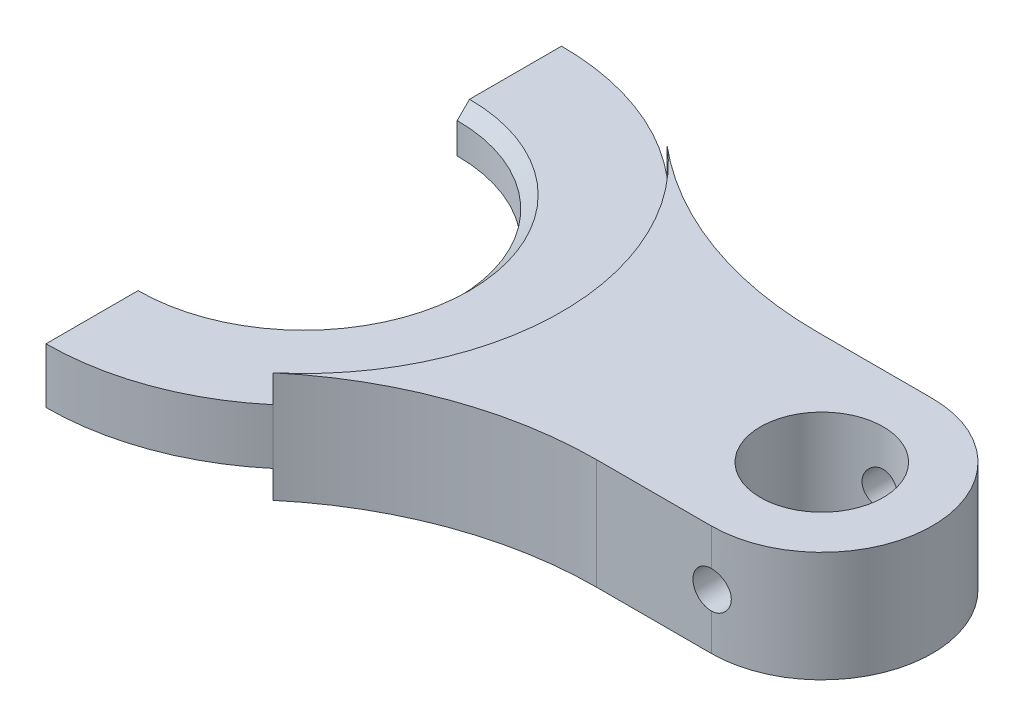
SolidWorks part; units mm, degrees
ref_plane "前视基准面" through (0, 0, 0) normal (0, 0, 1) x (1, 0, 0)
ref_plane "上视基准面" through (0, 0, 0) normal (0, 1, 0) x (1, 0, 0)
ref_plane "右视基准面" through (0, 0, 0) normal (1, 0, 0) x (0, 0, -1)
other "Configuration Table"
sketch "草图1" plane through (0, 0, 0) normal (0, 1, 0) x (1, 0, 0)
  line L0 (0, 9) -> (-9.3366, 9)
  line L1 (0, -9) -> (-9.3366, -9)
  line L2 (-42.2, 21) -> (-42.2, 12.5)
  line L3 (-42.2, -12.5) -> (-42.2, -21)
  arc A0 (0, -9) -> (0, 9) centre (0, 0) ccw
  arc A1 (-28.668, 16.0588) -> (-42.2, 21) centre (-42.2, 0) ccw
  arc A2 (-9.3366, 9) -> (-28.668, 16.0588) centre (-9.3366, 39) cw
  arc A3 (-9.3366, -9) -> (-28.668, -16.0588) centre (-9.3366, -39) ccw
  circle A4 centre (0, 0) radius 5
  arc A5 (-42.2, -12.5) -> (-42.2, 12.5) centre (-42.2, 0) ccw
  arc A6 (-42.2, -21) -> (-28.668, -16.0588) centre (-42.2, 0) ccw
  dimension "D1" = 18
  dimension "D2" = 42
  dimension "D3" = 42.2
  dimension "D4" = 30
  dimension "D5" = 10
  dimension "D6" = 25
extrude "凸台-拉伸1" add sketch "草图1" along normal mid plane 9
sketch "草图2" plane through (0, 4.5, 0) normal (0, 1, 0) x (1, 0, 0)
  line L0 (-42.2, -12.5) -> (-42.2, -21) construction
  line L1 (-42.2, 21) -> (-42.2, 12.5) construction
  line L2 (-42.2, -12.5) -> (-42.2, -21)
  line L3 (-42.2, 21) -> (-42.2, 12.5)
  arc A0 (-28.668, 16.0588) -> (-42.2, 21) centre (-42.2, 0) ccw construction
  arc A1 (-42.2, -21) -> (-42.2, 21) centre (-42.2, 0) ccw
  arc A3 (-42.2, -12.5) -> (-42.2, 12.5) centre (-42.2, 0) ccw construction
  arc A4 (-42.2, -12.5) -> (-42.2, 12.5) centre (-42.2, 0) ccw
  point P3 (-42.2, -21)
extrude "切除-拉伸1" cut sketch "草图2" against normal blind 2.25
mirror "镜向1" about plane through (0, 0, 0) normal (0, 1, 0) of "切除-拉伸1"
chamfer "倒角1" distance 1 angle 45 2 edges at (-29.7, -2.25, 0) (-29.7, 2.25, 0)
sketch "草图3" plane through (0, 0, 0) normal (0, 0, 1) x (1, 0, 0)
  circle A0 centre (0, 0) radius 1.5
  dimension "D1" = 3
extrude "切除-拉伸2" cut sketch "草图3" against normal mid plane 33.25
